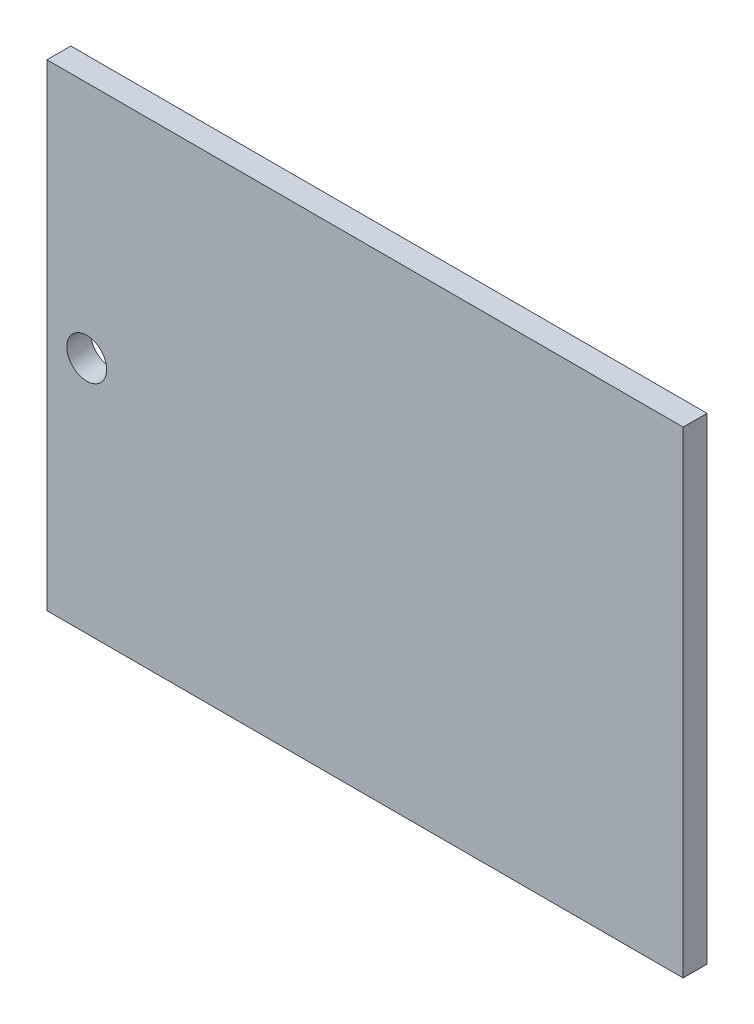
SolidWorks part; units mm, degrees
ref_plane "Front Plane" through (0, 0, 0) normal (0, 0, 1) x (1, 0, 0)
ref_plane "Top Plane" through (0, 0, 0) normal (0, 1, 0) x (1, 0, 0)
ref_plane "Right Plane" through (0, 0, 0) normal (1, 0, 0) x (0, 0, -1)
sketch "Sketch1" plane through (0, 0, 0) normal (0, 0, 1) x (1, 0, 0)
  line L1 (-20, -15) -> (20, -15)
  line L2 (-20, -15) -> (-20, 15)
  line L3 (-20, 15) -> (20, 15)
  line L4 (20, -15) -> (20, 15)
  line L5 (-20, -15) -> (20, 15) construction
  line L6 (-20, 15) -> (20, -15) construction
  point P0 (0, 0)
  dimension "D1" = 40
  dimension "D2" = 30
extrude "Boss-Extrude2" add sketch "Sketch1" along normal blind 1.5
sketch "Sketch2" plane through (0, 0, 1.5) normal (0, 0, 1) x (1, 0, 0)
  line L0 (-20, 15) -> (-20, -15) construction
  line L1 (-20, 0) -> (-17.5, 0) construction
  circle A0 centre (-17.5, 0) radius 1.25
  point P0 (-20, 0)
  dimension "D1" = 15
extrude "Cut-Extrude1" cut sketch "Sketch2" against normal through all
